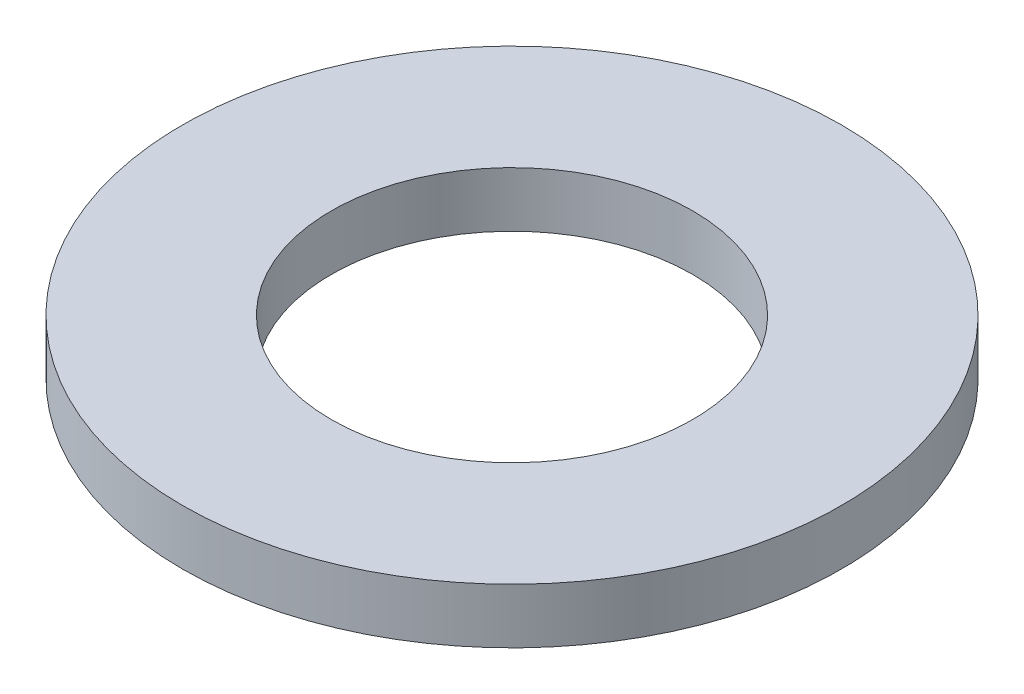
SolidWorks part; units mm, degrees
ref_plane "Front Plane" through (0, 0, 0) normal (0, 0, 1) x (1, 0, 0)
ref_plane "Top Plane" through (0, 0, 0) normal (0, 1, 0) x (1, 0, 0)
ref_plane "Right Plane" through (0, 0, 0) normal (1, 0, 0) x (0, 0, -1)
sketch "Sketch2" plane through (0, 0, 0) normal (0, 1, 0) x (1, 0, 0)
  circle A0 centre (0, 0) radius 37.973
  circle A1 centre (0, 0) radius 20.828
  dimension "D1" = 75.946
  dimension "D2" = 41.656
extrude "Boss-Extrude1" add sketch "Sketch2" along normal mid plane 6.35
